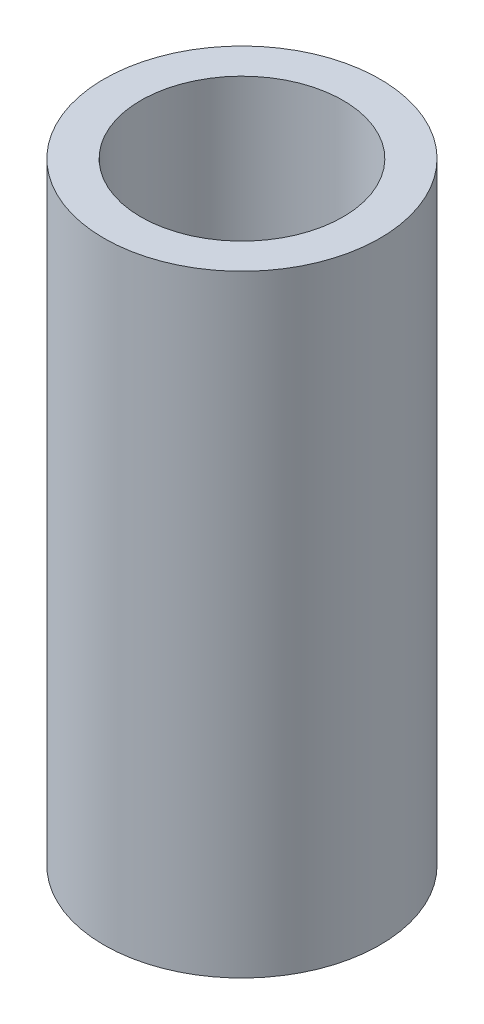
SolidWorks part; units mm, degrees
material "AISI 316 Stainless Steel Sheet (SS)"
ref_plane "Front Plane" through (0, 0, 0) normal (0, 0, 1) x (1, 0, 0)
ref_plane "Top Plane" through (0, 0, 0) normal (0, 1, 0) x (1, 0, 0)
ref_plane "Right Plane" through (0, 0, 0) normal (1, 0, 0) x (0, 0, -1)
sketch "Sketch1" plane through (0, 0, 0) normal (0, 1, 0) x (1, 0, 0)
  circle A0 centre (0, 0) radius 0.4508
  circle A1 centre (0, 0) radius 0.3302
  dimension "D1" = 0.6604
  dimension "D2" = 0.9017
extrude "Boss-Extrude1" add sketch "Sketch1" along normal blind 2 contours A0 A1
